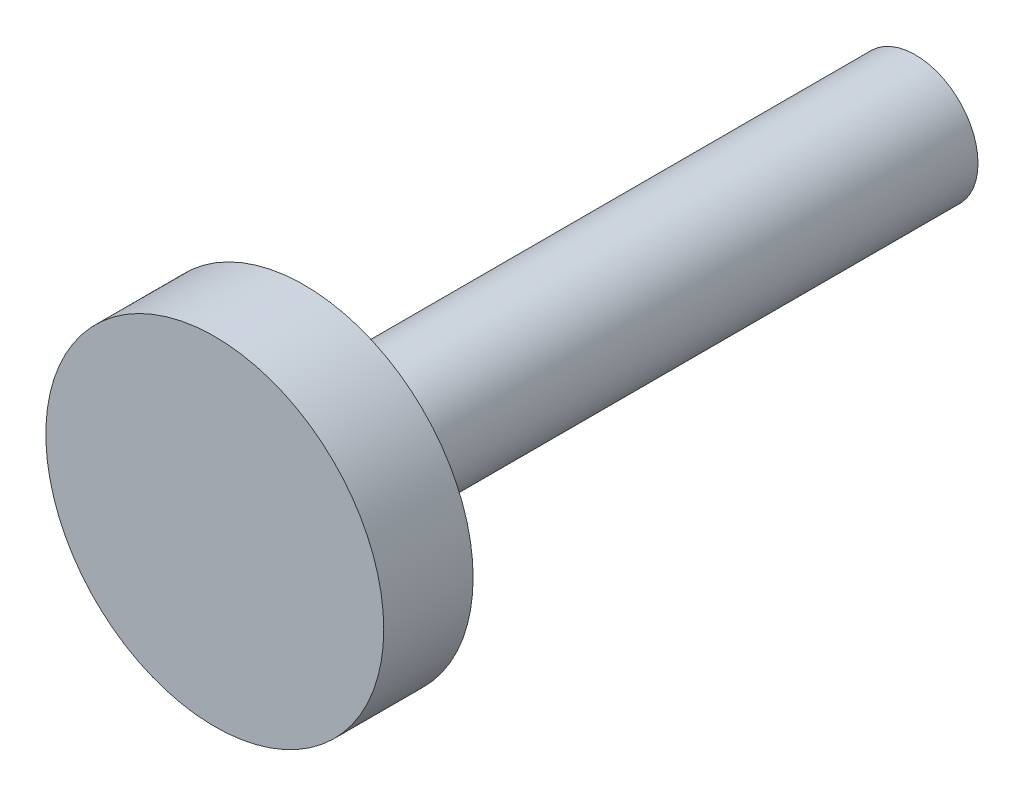
SolidWorks part; units mm, degrees
ref_plane "Front Plane" through (0, 0, 0) normal (0, 0, 1) x (1, 0, 0)
ref_plane "Top Plane" through (0, 0, 0) normal (0, 1, 0) x (1, 0, 0)
ref_plane "Right Plane" through (0, 0, 0) normal (1, 0, 0) x (0, 0, -1)
sketch "Sketch1" plane through (0, 0, 0) normal (0, 0, 1) x (1, 0, 0)
  circle A0 centre (0, 0) radius 3.5
  dimension "D1" = 7
extrude "Boss-Extrude1" add sketch "Sketch1" along normal blind 34.2
sketch "Sketch2" plane through (0, 0, 34.2) normal (0, 0, 1) x (1, 0, 0)
  circle A0 centre (0, 0) radius 9.453
  dimension "D1" = 18.906
extrude "Boss-Extrude2" add sketch "Sketch2" along normal blind 5
sketch "Sketch3" plane through (0, 0, 0) normal (0, 0, -1) x (-1, 0, 0)
  line L1 (-1.9434, 1.5726) -> (-2.3336, -0.8967)
  line L2 (-2.3336, -0.8967) -> (-0.3902, -2.4694)
  line L3 (-0.3902, -2.4694) -> (1.9434, -1.5726)
  line L4 (1.9434, -1.5726) -> (2.3336, 0.8967)
  line L5 (2.3336, 0.8967) -> (0.3902, 2.4694)
  line L6 (0.3902, 2.4694) -> (-1.9434, 1.5726)
  circle A0 centre (0, 0) radius 2.1651 construction
  dimension "D1" = 5
extrude "Cut-Extrude1" cut sketch "Sketch3" against normal blind 1.92
sketch "Sketch4" plane through (0, 0, 1.92) normal (0, 0, -1) x (-1, 0, 0)
  circle A0 centre (0, 0) radius 1
  dimension "D1" = 2
extrude "Cut-Extrude2" cut sketch "Sketch4" against normal blind 10
